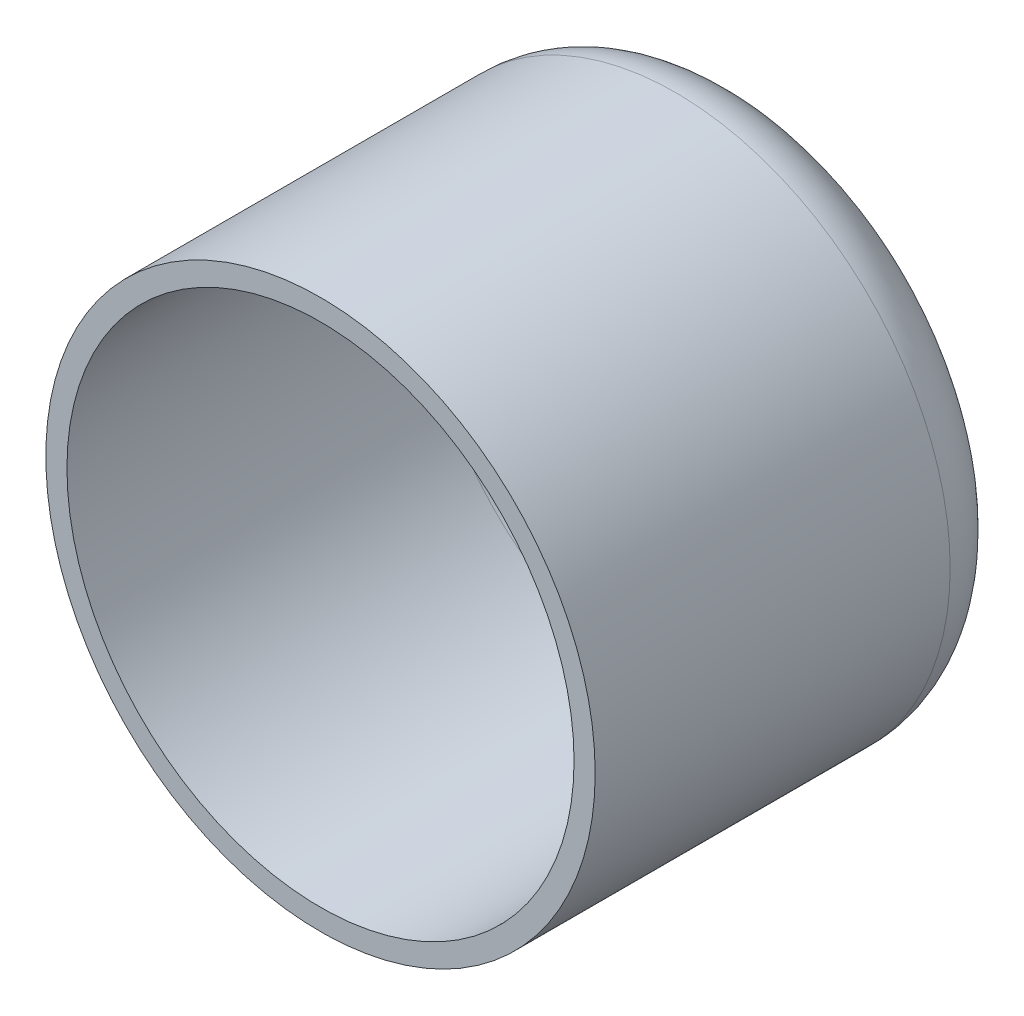
SolidWorks part; units mm, degrees
material "ABS"
ref_plane "Front Plane" through (0, 0, 0) normal (0, 0, 1) x (1, 0, 0)
ref_plane "Top Plane" through (0, 0, 0) normal (0, 1, 0) x (1, 0, 0)
ref_plane "Right Plane" through (0, 0, 0) normal (1, 0, 0) x (0, 0, -1)
sketch "Sketch2" plane through (0, 0, 0) normal (0, 0, 1) x (1, 0, 0)
  circle A0 centre (0, 0) radius 10.3187
  dimension "D1" = 20.6375
extrude "Boss-Extrude1" add sketch "Sketch2" along normal blind 15.875
fillet "Fillet1" radius 2.54 1 edges at (10.3187, 0, 0)
shell "Shell1" thickness 0.7937
